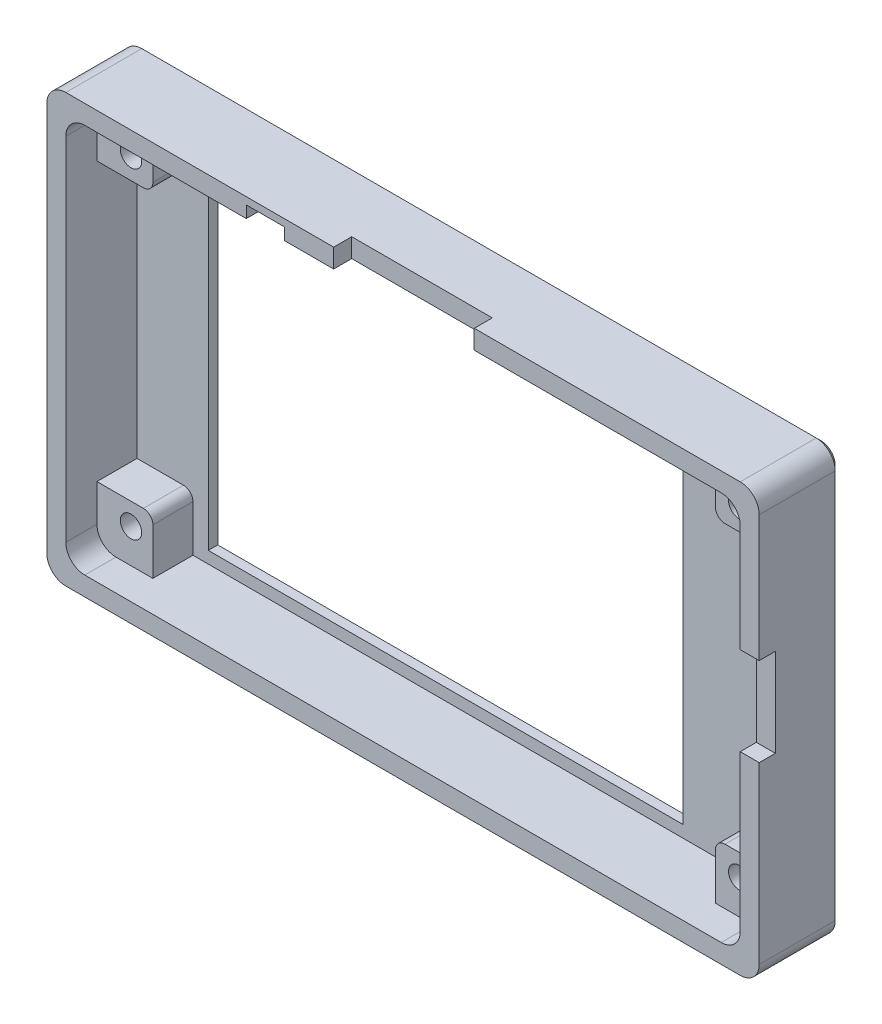
SolidWorks part; units mm, degrees
ref_plane "Přední rovina" through (0, 0, 0) normal (0, 0, 1) x (1, 0, 0)
ref_plane "Horní rovina" through (0, 0, 0) normal (0, 1, 0) x (1, 0, 0)
ref_plane "Pravá rovina" through (0, 0, 0) normal (1, 0, 0) x (0, 0, -1)
sketch "Skica1" plane through (0, 0, 0) normal (0, 0, 1) x (1, 0, 0)
  line L1 (-37.5, -22.5) -> (37.5, -22.5)
  line L2 (-37.5, -22.5) -> (-37.5, 22.5)
  line L3 (-37.5, 22.5) -> (37.5, 22.5)
  line L4 (37.5, -22.5) -> (37.5, 22.5)
  line L5 (-37.5, -22.5) -> (37.5, 22.5) construction
  line L6 (-37.5, 22.5) -> (37.5, -22.5) construction
  point P0 (0, 0)
  dimension "D1" = 75
  dimension "D2" = 45
extrude "Přidat vysunutím1" add sketch "Skica1" along normal blind 13
sketch "Skica2" plane through (0, 0, 13) normal (0, 0, 1) x (1, 0, 0)
  line L0 (37.5, 22.5) -> (-37.5, 22.5) construction
  line L1 (-35.5, -20.5) -> (35.5, -20.5)
  line L2 (-35.5, -20.5) -> (-35.5, 20.5)
  line L3 (-35.5, 20.5) -> (35.5, 20.5)
  line L4 (35.5, -20.5) -> (35.5, 20.5)
  line L5 (-35.5, -20.5) -> (35.5, 20.5) construction
  line L6 (-35.5, 20.5) -> (35.5, -20.5) construction
  line L7 (37.5, -22.5) -> (37.5, 22.5) construction
  point P0 (0, 0)
  dimension "D1" = 2
  dimension "D2" = 2
extrude "Odebrat vysunutím1" cut sketch "Skica2" against normal blind 12
fillet "Zaoblit1" radius 2 8 edges at (37.5, 22.5, 6.5) (37.5, -22.5, 6.5) (-37.5, -22.5, 6.5) (-37.5, 22.5, 6.5) (35.5, -20.5, 7) (35.5, 20.5, 7) (-35.5, -20.5, 7) (-35.5, 20.5, 7)
chamfer "Zkosení2" distance 0.5 angle 45 8 edges at (-36.9142, 21.9142, 0) (-37.5, 0, 0) (-36.9142, -21.9142, 0) (0, -22.5, 0) (36.9142, -21.9142, 0) (37.5, 0, 0) (36.9142, 21.9142, 0) (0, 22.5, 0)
sketch "Skica3" plane through (0, 0, 0) normal (0, 0, -1) x (-1, 0, 0)
  line L1 (-22, -19.25) -> (28, -19.25)
  line L2 (-22, -19.25) -> (-22, 19.25)
  line L3 (-22, 19.25) -> (28, 19.25)
  line L4 (28, -19.25) -> (28, 19.25)
  line L5 (-22, -19.25) -> (28, 19.25) construction
  line L6 (-22, 19.25) -> (28, -19.25) construction
  line L9 (-37.5, -20.5) -> (-37.5, 20.5) construction
  line L13 (-35.5, 22.5) -> (35.5, 22.5) construction
  point P0 (3, 0)
  dimension "D1" = 19.25
  dimension "D2" = 25
  dimension "D3" = 15.5
  dimension "D4" = 3.25
extrude "Odebrat vysunutím2" cut sketch "Skica3" against normal mid plane 12
sketch "Skica4" plane through (0, 0, 1) normal (0, 0, 1) x (1, 0, 0)
  line L1 (-29.6142, 14.6142) -> (-36.9142, 14.6142)
  line L2 (-29.6142, 14.6142) -> (-29.6142, 21.9142)
  line L3 (-29.6142, 21.9142) -> (-36.9142, 21.9142)
  line L4 (-36.9142, 14.6142) -> (-36.9142, 21.9142)
  line L5 (-36.9142, -21.9142) -> (-29.6142, -21.9142)
  line L6 (-36.9142, -21.9142) -> (-36.9142, -14.6142)
  line L7 (-36.9142, -14.6142) -> (-29.6142, -14.6142)
  line L8 (-29.6142, -21.9142) -> (-29.6142, -14.6142)
  line L9 (36.9142, -21.9142) -> (29.6142, -21.9142)
  line L10 (36.9142, -21.9142) -> (36.9142, -14.6142)
  line L11 (36.9142, -14.6142) -> (29.6142, -14.6142)
  line L12 (29.6142, -21.9142) -> (29.6142, -14.6142)
  line L13 (36.9142, 21.9142) -> (29.6142, 21.9142)
  line L14 (36.9142, 21.9142) -> (36.9142, 14.6142)
  line L15 (36.9142, 14.6142) -> (29.6142, 14.6142)
  line L16 (29.6142, 21.9142) -> (29.6142, 14.6142)
  arc A1 (-37.5, -20.5) -> (-35.5, -22.5) centre (-35.5, -20.5) ccw construction
  arc A2 (-35.5, 22.5) -> (-37.5, 20.5) centre (-35.5, 20.5) ccw construction
  arc A3 (35.5, -22.5) -> (37.5, -20.5) centre (35.5, -20.5) ccw construction
  arc A4 (37.5, 20.5) -> (35.5, 22.5) centre (35.5, 20.5) ccw construction
  dimension "D1" = 7.3
  dimension "D2" = 7.3
  dimension "D3" = 7.3
  dimension "D4" = 7.3
  dimension "D5" = 7.3
  dimension "D6" = 7.3
  dimension "D7" = 7.3
  dimension "D8" = 7.3
extrude "Přidat vysunutím2" add sketch "Skica4" along normal blind 4.22
fillet "Zaoblit2" radius 1 4 edges at (29.6142, -14.6142, 3.11) (29.6142, 14.6142, 3.11) (-29.6142, -14.6142, 3.11) (-29.6142, 14.6142, 3.11)
sketch "Skica5" plane through (0, 0, 13) normal (0, 0, 1) x (1, 0, 0)
  line L1 (34.1198, 7.2) -> (39.3994, 7.2)
  line L2 (34.1198, 7.2) -> (34.1198, -2.1)
  line L3 (34.1198, -2.1) -> (39.3994, -2.1)
  line L4 (39.3994, 7.2) -> (39.3994, -2.1)
  line L5 (-35.5, -22.5) -> (35.5, -22.5) construction
  dimension "D1" = 20.4
  dimension "D2" = 9.3
sketch "Skica6" plane through (0, -22.5, 0) normal (0, -1, 0) x (1, 0, 0)
  line L0 (35.5, 0) -> (-35.5, 0) construction
  line L1 (-48.5537, 25.4141) -> (43.6554, 25.4141)
  line L2 (-48.5537, 25.4141) -> (-48.5537, 8.5)
  line L3 (-48.5537, 8.5) -> (43.6554, 8.5)
  line L4 (43.6554, 25.4141) -> (43.6554, 8.5)
  dimension "D1" = 8.5
extrude "Odebrat vysunutím3" cut sketch "Skica6" against normal blind 64.22
extrude "Odebrat vysunutím4" cut sketch "Skica5" against normal blind 6.2
sketch "Skica7" plane through (0, 0, 8.5) normal (0, 0, 1) x (1, 0, 0)
  line L0 (-37.5, -20.5) -> (-37.5, 20.5) construction
  line L1 (-16.5, 21.75) -> (-12.5, 21.75)
  line L2 (-16.5, 21.75) -> (-16.5, 14.4358)
  line L3 (-16.5, 14.4358) -> (-12.5, 14.4358)
  line L4 (-12.5, 21.75) -> (-12.5, 14.4358)
  line L5 (-35.5, 22.5) -> (35.5, 22.5) construction
  dimension "D1" = 21
  dimension "D2" = 4
  dimension "D3" = 0.75
extrude "Odebrat vysunutím5" cut sketch "Skica7" against normal blind 1.9
sketch "Skica8" plane through (0, 0, 8.5) normal (0, 0, 1) x (1, 0, 0)
  line L0 (37.5, 20.5) -> (37.5, 7.2) construction
  line L1 (-7.3, 24.2167) -> (7.5, 24.2167)
  line L2 (-7.3, 24.2167) -> (-7.3, 16.9244)
  line L3 (-7.3, 16.9244) -> (7.5, 16.9244)
  line L4 (7.5, 24.2167) -> (7.5, 16.9244)
  dimension "D1" = 30
  dimension "D2" = 14.8
extrude "Odebrat vysunutím6" cut sketch "Skica8" against normal blind 1.9
sketch "Skica9" plane through (0, 0, 5.22) normal (0, 0, 1) x (1, 0, 0)
  line L0 (-29.6142, 15.6142) -> (-29.6142, 20.5) construction
  line L1 (-35.5, 14.6142) -> (-30.6142, 14.6142) construction
  line L2 (30.6142, 14.6142) -> (35.5, 14.6142) construction
  line L3 (29.6142, -15.6142) -> (29.6142, -20.5) construction
  line L6 (-29.6142, -20.5) -> (-29.6142, -15.6142) construction
  line L8 (-30.6142, -14.6142) -> (-35.5, -14.6142) construction
  line L10 (35.5, -14.6142) -> (30.6142, -14.6142) construction
  line L11 (29.6142, 20.5) -> (29.6142, 15.6142) construction
  circle A0 centre (-31.9142, 16.9142) radius 1.125
  circle A1 centre (-31.9142, -16.9142) radius 1.125
  circle A2 centre (32.1142, -16.9142) radius 1.125
  circle A3 centre (32.1142, 16.9142) radius 1.125
  dimension "D1" = 2.25
  dimension "D4" = 2.25
  dimension "D5" = 2.25
  dimension "D6" = 2.25
  dimension "D2" = 2.3
  dimension "D3" = 2.3
  dimension "D7" = 2.3
  dimension "D8" = 2.5
  dimension "D9" = 2.3
  dimension "D10" = 2.3
  dimension "D11" = 2.3
  dimension "D12" = 2.5
extrude "Odebrat vysunutím7" cut sketch "Skica9" against normal blind 3
